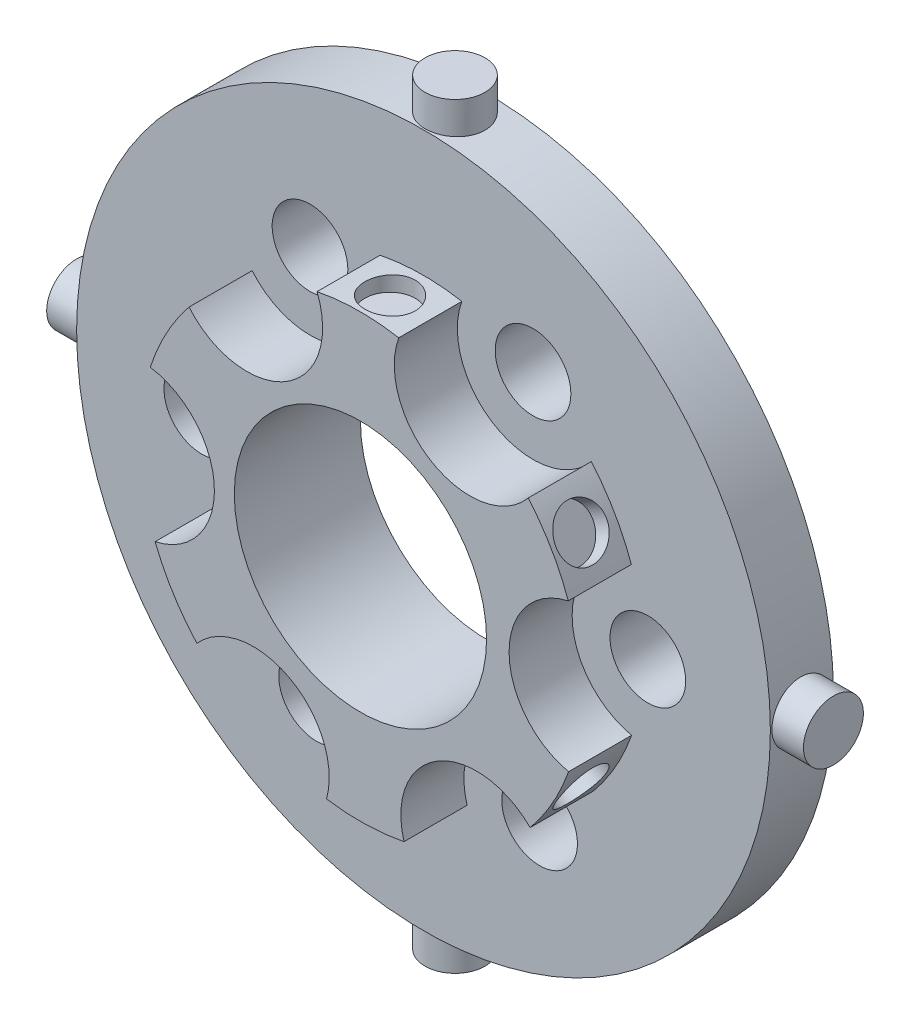
SolidWorks part; units mm, degrees
ref_plane "Alzado" through (0, 0, 0) normal (0, 0, 1) x (1, 0, 0)
ref_plane "Planta" through (0, 0, 0) normal (0, 1, 0) x (1, 0, 0)
ref_plane "Vista lateral" through (0, 0, 0) normal (1, 0, 0) x (0, 0, -1)
sketch "Croquis1" plane through (0, 0, 0) normal (0, 0, 1) x (1, 0, 0)
  circle A0 centre (0, 0) radius 20
  circle A2 centre (0, 0) radius 55
  dimension "D1" = 40
  dimension "D3" = 110
extrude "Saliente-Extruir1" add sketch "Croquis1" along normal blind 10
sketch "Croquis2" plane through (0, 0, 0) normal (0, 0, 1) x (1, 0, 0)
  line L0 (0, 68.982) -> (0, -84.1106) construction
  line L1 (-72.9335, 0) -> (100.2554, 0) construction
  arc A0 (-27.1741, 22.0583) -> (-33.3181, 10.7193) centre (0, 0) ccw
  circle A1 centre (0, 0) radius 20
  circle A2 centre (17.3687, 30.3863) radius 6
  arc A3 (6.084, 34.4672) -> (26.6118, 22.7335) centre (17.3687, 30.3863) ccw
  circle A4 centre (35.5702, 0.0631) radius 6
  arc A5 (32.9596, 11.7757) -> (33.0011, -11.6587) centre (35.5702, 0.0631) ccw
  circle A6 centre (18.4103, -30.8614) radius 6
  arc A7 (26.9051, -22.3856) -> (6.9165, -34.3098) centre (18.4103, -30.8614) ccw
  circle A8 centre (-16.9511, -31.4628) radius 6
  arc A9 (-5.3647, -34.5864) -> (-25.9329, -23.505) centre (-16.9511, -31.4628) ccw
  circle A10 centre (-35.1525, -1.1396) radius 6
  arc A11 (-32.5538, -12.8548) -> (-33.3181, 10.7193) centre (-35.1525, -1.1396) ccw
  circle A12 centre (-17.9926, 29.7849) radius 6
  arc A13 (-27.1741, 22.0583) -> (-6.8813, 34.3169) centre (-17.9926, 29.7849) ccw
  arc A14 (6.084, 34.4672) -> (-6.8813, 34.3169) centre (0, 0) ccw
  arc A15 (32.9596, 11.7757) -> (26.6118, 22.7335) centre (0, 0) ccw
  arc A16 (26.9051, -22.3856) -> (33.0011, -11.6587) centre (0, 0) ccw
  arc A17 (-5.3647, -34.5864) -> (6.9165, -34.3098) centre (0, 0) ccw
  arc A18 (-32.5538, -12.8548) -> (-25.9329, -23.505) centre (0, 0) ccw
  point P28 (0.2088, -0.5383)
  dimension "D1" = 70
  dimension "D2" = 12
  dimension "D3" = 24
extrude "Saliente-Extruir2" add sketch "Croquis2" along normal blind 20
sketch "Croquis3" plane through (0, 0, 20) normal (0, 0, 1) x (1, 0, 0)
  circle A0 centre (-17.9926, 29.7849) radius 6
  circle A1 centre (-35.1525, -1.1396) radius 6
  circle A2 centre (-16.9511, -31.4628) radius 6
  circle A3 centre (18.4103, -30.8614) radius 6
  circle A4 centre (35.5702, 0.0631) radius 6
  circle A5 centre (17.3687, 30.3863) radius 6
extrude "Cortar-Extruir2" cut sketch "Croquis3" against normal through all
ref_plane "Plano1" through (0, 55, 0) normal (0, 1, 0) x (1, 0, 0)
sketch "Croquis4" plane through (0, 55, 0) normal (0, 1, 0) x (1, 0, 0)
  circle A0 centre (0, -5.0018) radius 4.75
  dimension "D1" = 9.5
extrude "Saliente-Extruir3" add sketch "Croquis4" along normal mid plane 10
pattern_circular "MatrizC1" count 4 over 360 about axis through (0, 0, 0) along (0, 0, 1) of "Saliente-Extruir3"
ref_plane "Plano2" through (0, 35, 0) normal (0, 1, 0) x (1, 0, 0)
sketch "Croquis5" plane through (0, 35, 0) normal (0, 1, 0) x (1, 0, 0)
  circle A0 centre (0, -15.3072) radius 4
  dimension "D1" = 8
extrude "Cortar-Extruir3" cut sketch "Croquis5" against normal mid plane 5
pattern_circular "MatrizC2" count 6 over 360 about axis through (0, 0, 0) along (0, 0, 1) of "Cortar-Extruir3"
